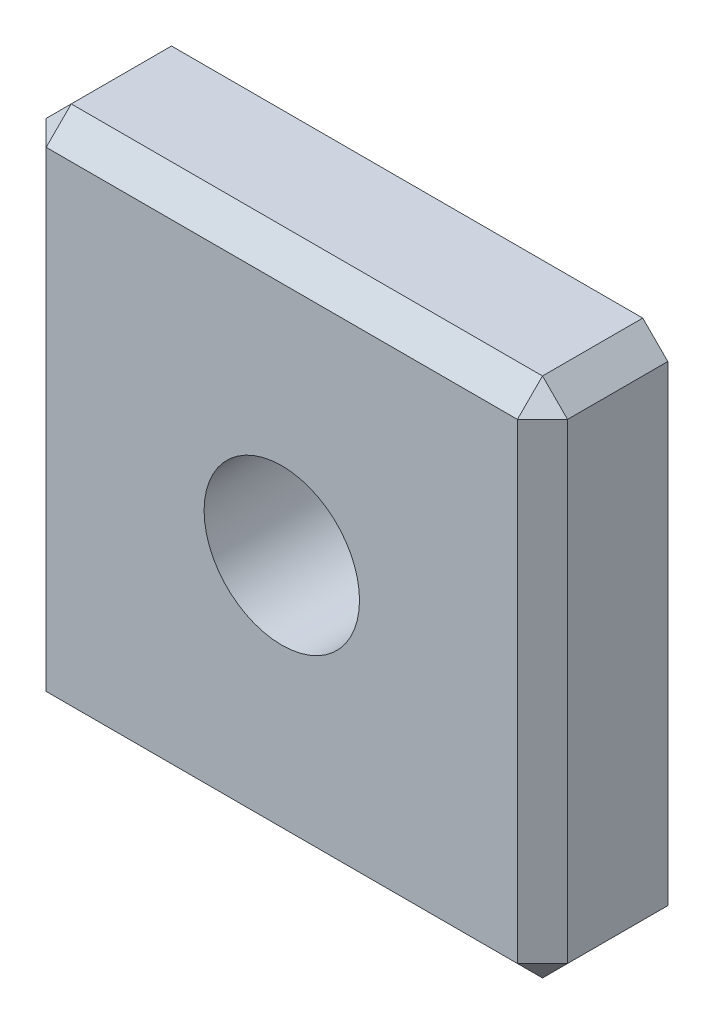
SolidWorks part; units mm, degrees
ref_plane "Plan de face" through (0, 0, 0) normal (0, 0, 1) x (1, 0, 0)
ref_plane "Plan de dessus" through (0, 0, 0) normal (0, 1, 0) x (1, 0, 0)
ref_plane "Plan de droite" through (0, 0, 0) normal (1, 0, 0) x (0, 0, -1)
sketch "Esquisse2" plane through (0, 0, 0) normal (0, 0, 1) x (1, 0, 0)
  line L1 (0, 0) -> (20.8, 0)
  line L2 (0, 0) -> (0, 20.8)
  line L3 (0, 20.8) -> (20.8, 20.8)
  line L4 (20.8, 0) -> (20.8, 20.8)
  dimension "D1" = 20.8
  dimension "D2" = 20.8
extrude "Boss.-Extru.1" add sketch "Esquisse2" along normal blind 5
sketch "Esquisse4" plane through (0, 0, 5) normal (0, 0, 1) x (1, 0, 0)
  line L0 (0, 10.4) -> (20.8, 10.4) construction
  line L1 (0, 20.8) -> (0, 0) construction
  line L2 (20.8, 0) -> (20.8, 20.8) construction
  circle A0 centre (10.4, 10.4) radius 3.1
  dimension "D1" = 6.2
extrude "Enlèv. mat.-Extru.1" cut sketch "Esquisse4" against normal through all both and the other way through all
chamfer "Chanfrein1" distance 1 angle 45 8 edges at (10.4, 20.8, 5) (20.8, 10.4, 5) (10.4, 0, 5) (0, 10.4, 5) (0, 20.8, 2.5) (20.8, 20.8, 2.5) (20.8, 0, 2.5) (0, 0, 2.5)
